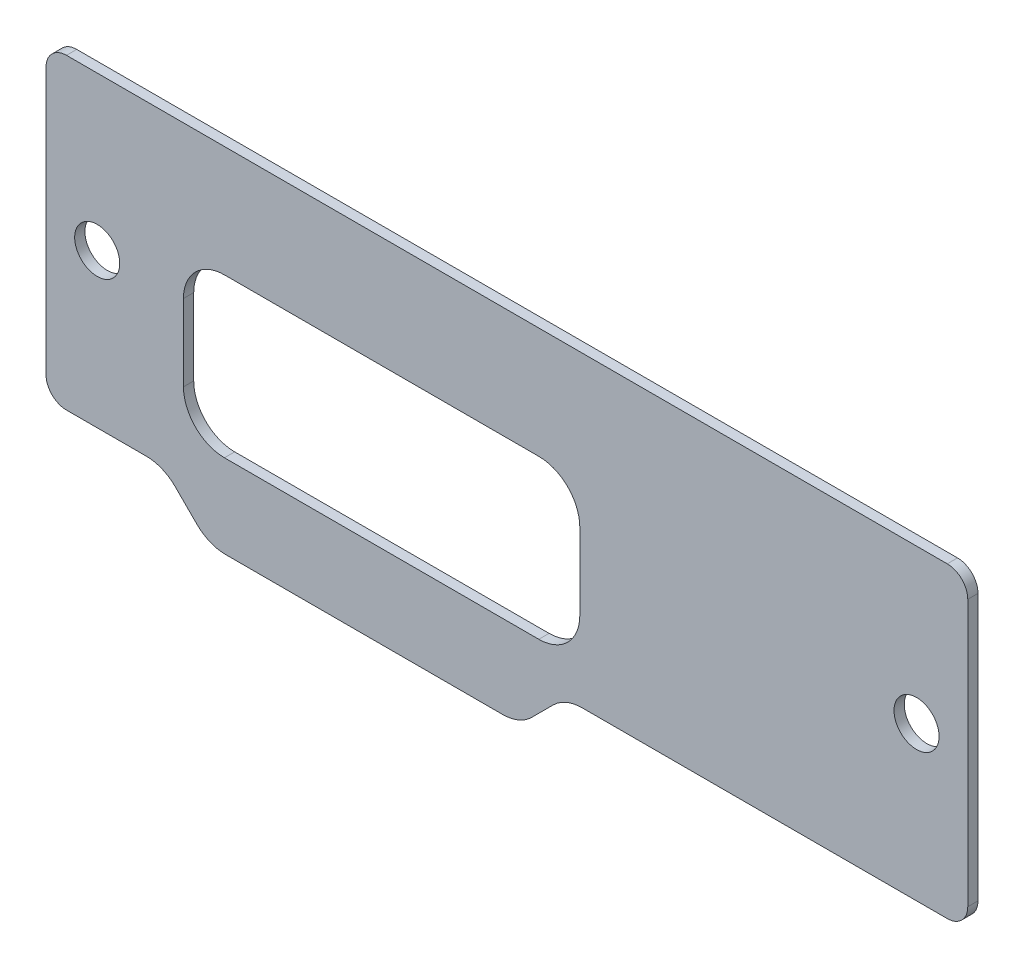
SolidWorks part; units mm, degrees
material "PA 类型 6"
ref_plane "前视基准面" through (0, 0, 0) normal (0, 0, 1) x (1, 0, 0)
ref_plane "上视基准面" through (0, 0, 0) normal (0, 1, 0) x (1, 0, 0)
ref_plane "右视基准面" through (0, 0, 0) normal (1, 0, 0) x (0, 0, -1)
sketch "草图1" plane through (0, 0, 0) normal (0, 0, 1) x (1, 0, 0)
  line L1 (-21.4884, 9.3368) -> (18.5116, 9.3368) construction
  line L2 (-21.4884, 9.3368) -> (-21.4884, -0.6632) construction
  line L3 (-21.4884, -0.6632) -> (18.5116, -0.6632) construction
  line L4 (18.5116, 9.3368) -> (18.5116, -0.6632) construction
  line L5 (-21.4884, 9.3368) -> (18.5116, -0.6632) construction
  line L6 (-21.4884, -0.6632) -> (18.5116, 9.3368) construction
  line L7 (-23.9884, 11.8368) -> (21.0116, 11.8368)
  line L8 (-23.9884, 11.8368) -> (-23.9884, -3.1632)
  line L9 (-23.9884, -3.1632) -> (21.0116, -3.1632)
  line L10 (21.0116, 11.8368) -> (21.0116, -3.1632)
  line L11 (-23.9884, 11.8368) -> (21.0116, -3.1632) construction
  line L12 (-23.9884, -3.1632) -> (21.0116, 11.8368) construction
  circle A0 centre (-21.4884, 9.3368) radius 1.1 construction
  circle A1 centre (-21.4884, -0.6632) radius 1.1 construction
  circle A2 centre (18.5116, -0.6632) radius 1.1 construction
  circle A3 centre (18.5116, 9.3368) radius 1.1 construction
  circle A4 centre (-21.4884, 4.3368) radius 1.1
  circle A5 centre (18.5116, 4.3368) radius 1.1
  point P0 (-1.4884, 4.3368)
  point P9 (-1.4884, 4.3368)
  dimension "D3" = 45
  dimension "D4" = 15
  dimension "D1" = 10
  dimension "D2" = 40
extrude "凸台-拉伸1" add sketch "草图1" along normal blind 0.5
sketch "草图2" plane through (0, 0, 0.5) normal (0, 0, 1) x (1, 0, 0)
  line L7 (-17.2774, 6.4097) -> (2.072, 6.4097)
  line L8 (-17.2774, 6.4097) -> (-17.2774, -1.3235)
  line L9 (-17.2774, -1.3235) -> (2.072, -1.3235)
  line L10 (2.072, 6.4097) -> (2.072, -1.3235)
  line L11 (-17.2774, 6.4097) -> (2.072, -1.3235) construction
  line L12 (-17.2774, -1.3235) -> (2.072, 6.4097) construction
  point P8 (-7.6027, 2.5431)
extrude "切除-拉伸1" cut sketch "草图2" against normal blind 1.5
fillet "圆角2" radius 1 4 edges at (21.0116, 11.8368, 0.25) (21.0116, -3.1632, 0.25) (-23.9884, -3.1632, 0.25) (-23.9884, 11.8368, 0.25)
fillet "圆角3" radius 2 4 edges at (2.072, 6.4097, 0.25) (2.072, -1.3235, 0.25) (-17.2774, -1.3235, 0.25) (-17.2774, 6.4097, 0.25)
sketch "草图3" plane through (0, 0, 0.5) normal (0, 0, 1) x (1, 0, 0)
  line L0 (-18.8396, -2.5877) -> (-16.0408, -5.3865)
  line L1 (-16.0408, -5.3865) -> (-0.8641, -5.3865)
  line L2 (-0.8641, -5.3865) -> (2.8881, -1.6343)
  line L3 (2.8881, -1.6343) -> (-18.8396, -2.5877)
  line L4 (-22.9884, -3.1632) -> (20.0116, -3.1632) construction
  dimension "D1" = 45
  dimension "D2" = 45
extrude "凸台-拉伸2" add sketch "草图3" against normal up to surface (0.5 mm away) up to face at (-7.6027, 2.5431, 0)
fillet "圆角4" radius 2 4 edges at (1.3592, -3.1632, 0.25) (-0.8641, -5.3865, 0.25) (-18.2641, -3.1632, 0.25) (-16.0408, -5.3865, 0.25)
